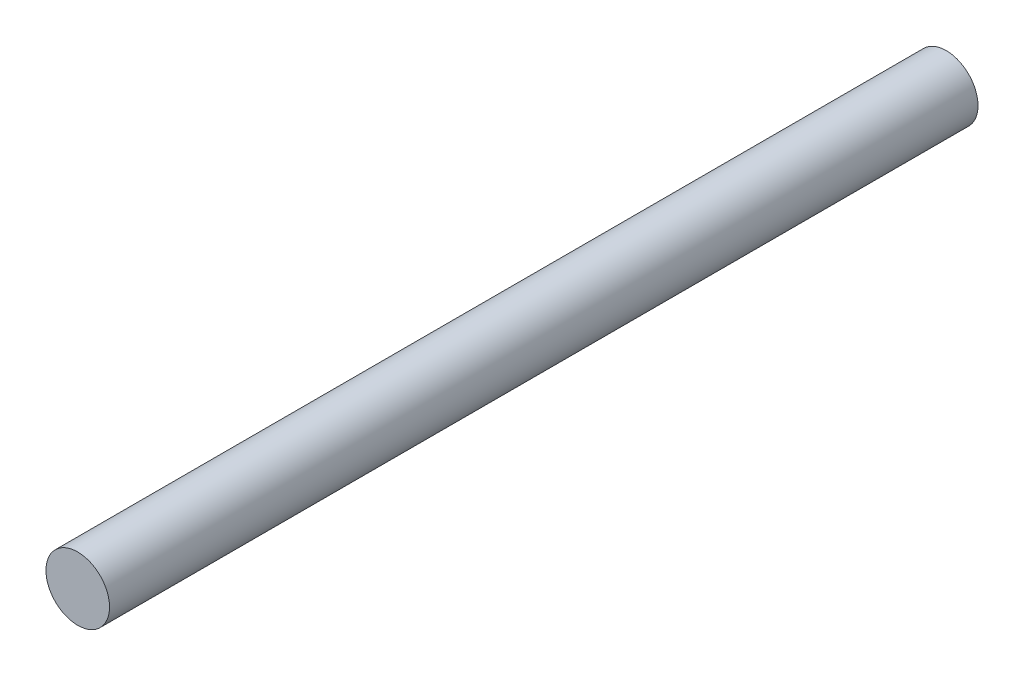
SolidWorks part; units mm, degrees
ref_plane "Front Plane" through (0, 0, 0) normal (0, 0, 1) x (1, 0, 0)
ref_plane "Top Plane" through (0, 0, 0) normal (0, 1, 0) x (1, 0, 0)
ref_plane "Right Plane" through (0, 0, 0) normal (1, 0, 0) x (0, 0, -1)
sketch "Sketch1" plane through (0, 0, 0) normal (0, 0, 1) x (1, 0, 0)
  circle A0 centre (0, 0) radius 1.94
  dimension "D1" = 3.88
extrude "Boss-Extrude1" add sketch "Sketch1" along normal blind 53
